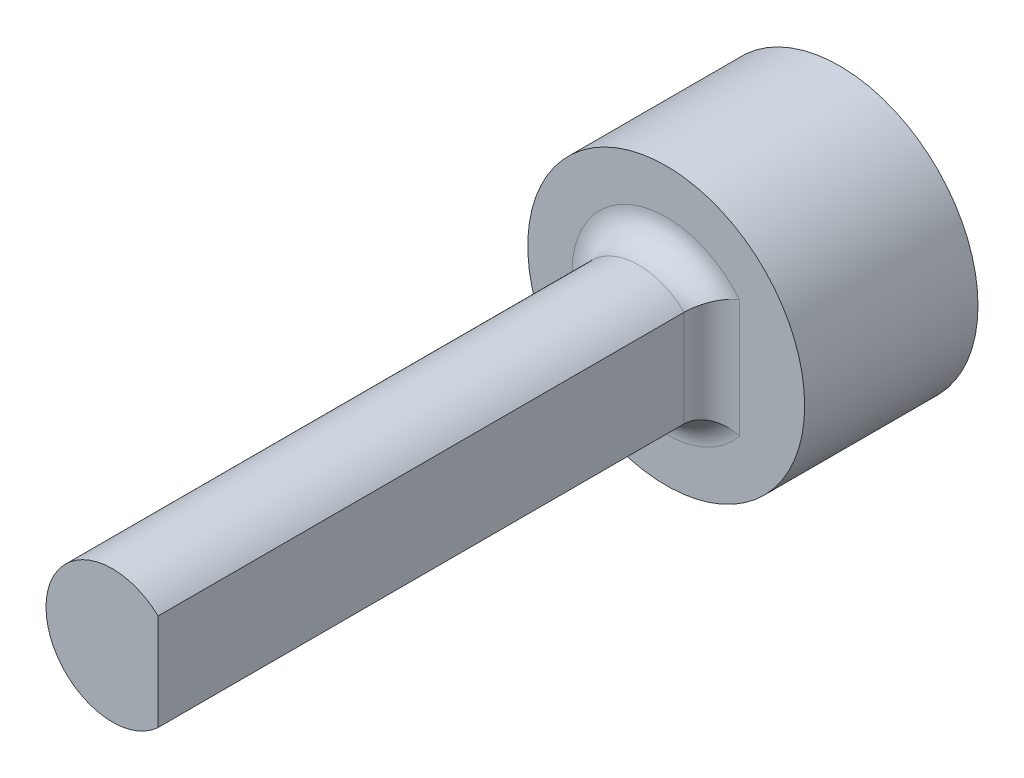
SolidWorks part; units mm, degrees
ref_plane "Front Plane" through (0, 0, 0) normal (0, 0, 1) x (1, 0, 0)
ref_plane "Top Plane" through (0, 0, 0) normal (0, 1, 0) x (1, 0, 0)
ref_plane "Right Plane" through (0, 0, 0) normal (1, 0, 0) x (0, 0, -1)
sketch "Sketch1" plane through (0, 0, 0) normal (0, 0, 1) x (1, 0, 0)
  line L1 (0, -2.7863) -> (2.413, -1.3931)
  line L2 (2.413, -1.3931) -> (2.413, 1.3931)
  line L3 (2.413, 1.3931) -> (0, 2.7863)
  line L4 (0, 2.7863) -> (-2.413, 1.3931)
  line L5 (-2.413, 1.3931) -> (-2.413, -1.3931)
  line L6 (-2.413, -1.3931) -> (0, -2.7863)
  circle A0 centre (0, 0) radius 4.7498
  circle A1 centre (0, 0) radius 2.413 construction
  circle A2 centre (0, 0) radius 6.35
  dimension "D1" = 9.4996
  dimension "D3" = 12.7
  dimension "D2" = 4.826
extrude "Boss-Extrude1" add sketch "Sketch1" along normal blind 6.1722 contours L5 L6 L1 L2 L3 L4 | A2 A0
sketch "Sketch2" plane through (0, 0, 6.1722) normal (0, 0, 1) x (1, 0, 0)
  circle A0 centre (0, 0) radius 6.35
extrude "Boss-Extrude2" add sketch "Sketch2" along normal blind 1.778
sketch "Sketch3" plane through (0, 0, 7.9502) normal (0, 0, 1) x (1, 0, 0)
  circle A0 centre (0, 0) radius 3.048
  dimension "D1" = 6.096
extrude "Boss-Extrude3" add sketch "Sketch3" along normal blind 25.4
sketch "Sketch4" plane through (0, 0, 33.3502) normal (0, 0, 1) x (1, 0, 0)
  line L0 (2.0931, 2.2156) -> (2.0931, -2.2156)
  circle A0 centre (0, 0) radius 3.048 construction
  arc A1 (2.0931, -2.2156) -> (2.0931, 2.2156) centre (0, 0) ccw
extrude "Cut-Extrude1" cut sketch "Sketch4" against normal up to surface (25.4 mm away) up to face at (3.048, 0, 7.9502)
fillet "Fillet1" radius 1.27 2 edges at (2.0931, 0, 7.9502) (-3.048, 0, 7.9502)
sketch "Sketch5" plane through (0, 0, 0) normal (0, 0, -1) x (-1, 0, 0)
  line L6 (2.413, -1.3931) -> (2.413, 1.3931)
  line L7 (2.413, 1.3931) -> (0, 2.7863)
  line L8 (0, 2.7863) -> (-2.413, 1.3931)
  line L9 (-2.413, 1.3931) -> (-2.413, -1.3931)
  line L10 (-2.413, -1.3931) -> (0, -2.7863)
  line L11 (0, -2.7863) -> (2.413, -1.3931)
  line L12 (2.413, -1.3931) -> (2.413, 1.3931)
  line L13 (2.413, 1.3931) -> (0, 2.7863)
  line L14 (0, 2.7863) -> (-2.413, 1.3931)
  line L15 (-2.413, 1.3931) -> (-2.413, -1.3931)
  line L16 (-2.413, -1.3931) -> (0, -2.7863)
  line L17 (0, -2.7863) -> (2.413, -1.3931)
  dimension "D1" = 0
extrude "Cut-Extrude2" cut sketch "Sketch5" against normal blind 2.54
